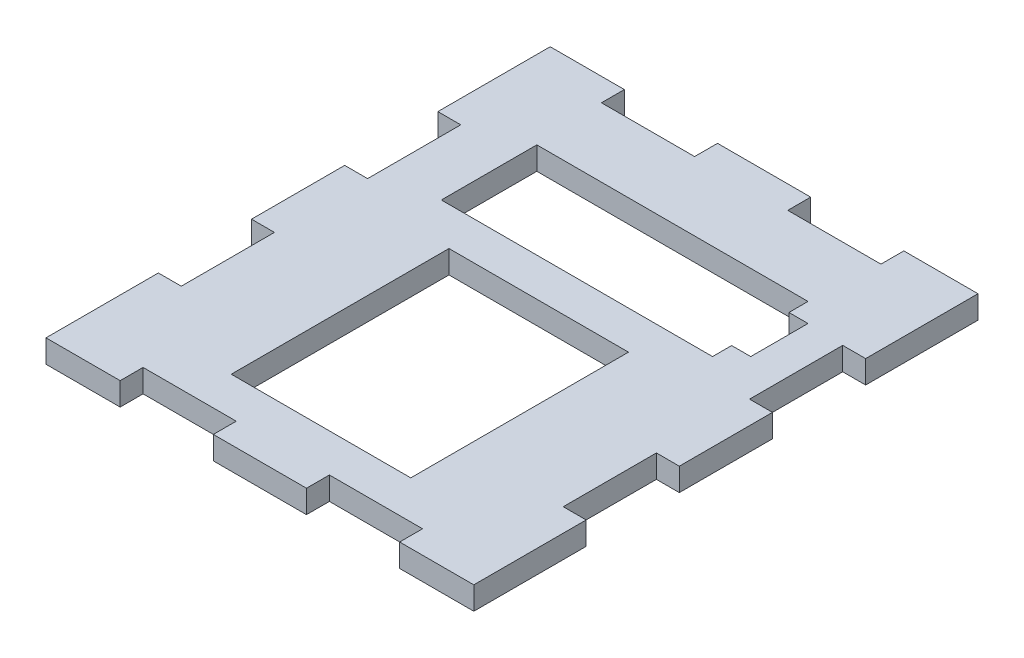
SolidWorks part; units mm, degrees
ref_plane "Front Plane" through (0, 0, 0) normal (0, 0, 1) x (1, 0, 0)
ref_plane "Top Plane" through (0, 0, 0) normal (0, 1, 0) x (1, 0, 0)
ref_plane "Right Plane" through (0, 0, 0) normal (1, 0, 0) x (0, 0, -1)
sketch "Sketch1" plane through (0, 0, 0) normal (0, 1, 0) x (1, 0, 0)
  line L0 (0, 135) -> (0, 105.585)
  line L1 (0, 105.585) -> (6, 105.585)
  line L2 (6, 105.585) -> (6, 81.195)
  line L3 (6, 81.195) -> (0, 81.195)
  line L4 (0, 81.195) -> (0, 56.805)
  line L5 (0, 56.805) -> (6, 56.805)
  line L6 (6, 56.805) -> (6, 32.415)
  line L7 (6, 32.415) -> (0, 32.415)
  line L8 (0, 32.415) -> (0, 8.025)
  line L9 (0, 8.025) -> (0, 3)
  line L10 (0, 3) -> (19.415, 3)
  line L11 (19.415, 3) -> (19.415, 9)
  line L12 (19.415, 9) -> (43.805, 9)
  line L13 (43.805, 9) -> (43.805, 3)
  line L14 (43.805, 3) -> (68.195, 3)
  line L15 (68.195, 3) -> (68.195, 9)
  line L16 (68.195, 9) -> (92.585, 9)
  line L17 (92.585, 9) -> (92.585, 3)
  line L18 (92.585, 3) -> (112, 3)
  line L19 (112, 3) -> (112, 32.415)
  line L20 (112, 32.415) -> (106, 32.415)
  line L21 (106, 32.415) -> (106, 56.805)
  line L22 (106, 56.805) -> (112, 56.805)
  line L23 (112, 56.805) -> (112, 81.195)
  line L24 (112, 81.195) -> (106, 81.195)
  line L25 (106, 81.195) -> (106, 105.585)
  line L26 (106, 105.585) -> (112, 105.585)
  line L27 (112, 105.585) -> (112, 129.975)
  line L28 (112, 129.975) -> (112, 135)
  line L29 (112, 135) -> (92.585, 135)
  line L30 (92.585, 135) -> (92.585, 129)
  line L31 (92.585, 129) -> (68.195, 129)
  line L32 (68.195, 129) -> (68.195, 135)
  line L33 (68.195, 135) -> (43.805, 135)
  line L34 (43.805, 135) -> (43.805, 129)
  line L35 (43.805, 129) -> (19.415, 129)
  line L36 (19.415, 129) -> (19.415, 135)
  line L37 (19.415, 135) -> (0, 135)
extrude "Boss-Extrude1" add sketch "Sketch1" along normal blind 6
sketch "Sketch2" plane through (0, 6, 0) normal (0, 1, 0) x (1, 0, 0)
  line L0 (106, 32.415) -> (106, 56.805) construction
  line L1 (20.5, 111) -> (91.5, 111)
  line L2 (20.5, 111) -> (20.5, 86)
  line L3 (20.5, 86) -> (91.5, 86)
  line L4 (96.5, 106) -> (96.5, 91)
  line L5 (32.5, 76) -> (79.5, 76)
  line L6 (32.5, 76) -> (32.5, 19)
  line L7 (32.5, 19) -> (79.5, 19)
  line L8 (79.5, 76) -> (79.5, 19)
  line L11 (106, 81.195) -> (106, 105.585) construction
  line L12 (96.5, 98.5) -> (96.5, 106)
  line L13 (68.195, 9) -> (92.585, 9) construction
  line L14 (96.5, 106) -> (91.5, 106)
  line L18 (91.5, 91) -> (96.5, 91)
  line L19 (96.5, 98.5) -> (96.5, 91)
  line L22 (96.5, 106) -> (91.5, 106)
  line L23 (91.5, 111) -> (91.5, 106)
  line L24 (91.5, 91) -> (96.5, 91)
  line L25 (91.5, 91) -> (91.5, 86)
  line L31 (96.5, 106) -> (96.5, 91)
  line L32 (91.5, 91) -> (91.5, 86)
  line L34 (20.5, 111) -> (91.5, 111)
  line L35 (20.5, 111) -> (20.5, 86)
  line L36 (20.5, 86) -> (91.5, 86)
  line L37 (91.5, 111) -> (91.5, 86)
  line L38 (91.5, 106) -> (96.5, 106)
  line L39 (91.5, 106) -> (91.5, 91)
  line L40 (91.5, 91) -> (96.5, 91)
  line L41 (96.5, 106) -> (96.5, 91)
  dimension "D2" = 57
  dimension "D3" = 47
  dimension "D4" = 26.5
  dimension "D5" = 71
  dimension "D6" = 9.5
  dimension "D7" = 10
  dimension "D8" = 10
  dimension "D9" = 15
  dimension "D10" = 5
  dimension "D11" = 25
  dimension "D12" = 14.5
extrude "Cut-Extrude1" cut sketch "Sketch2" against normal through all contours L2 L1 L4 L3 | L6 L5 L8 L7 | L35 L34 L37 L36 | L39 L38 L41 L40
